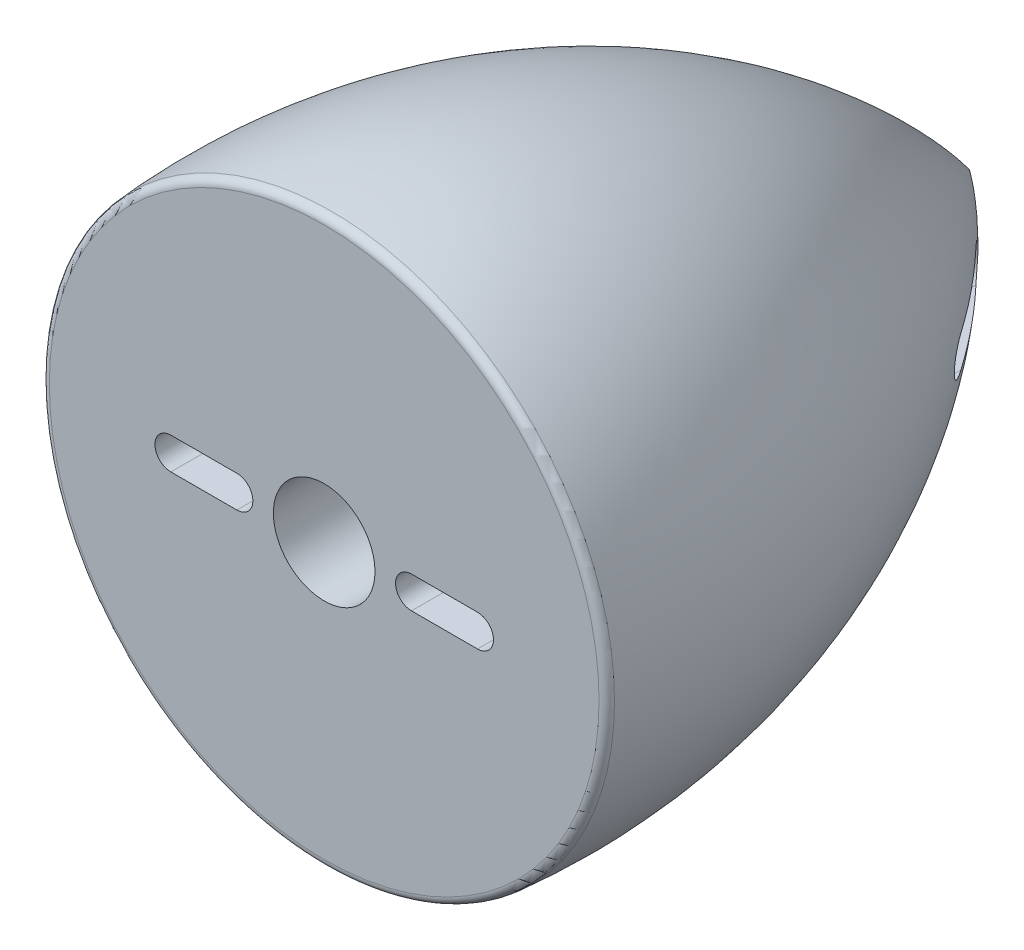
SolidWorks part; units mm, degrees
material "Pine"
ref_plane "Front Plane" through (0, 0, 0) normal (0, 0, 1) x (1, 0, 0)
ref_plane "Top Plane" through (0, 0, 0) normal (0, 1, 0) x (1, 0, 0)
ref_plane "Right Plane" through (0, 0, 0) normal (1, 0, 0) x (0, 0, -1)
ref_plane "Plane1" through (0, 0, -61.468) normal (0, 0, 1) x (1, 0, 0)
sketch "Sketch9" plane through (0, 0, 0) normal (1, 0, 0) x (0, 0, -1)
  line L3 (0, 0) -> (50.8, 0)
  line L4 (0, 0) -> (0, 22.225)
  arc A1 (0, 22.225) -> (50.8, 0) centre (5.1737, -35.1191) cw
  dimension "D1" = 22.225
  dimension "D2" = 50.8
revolve "Revolve2" add sketch "Sketch9" angle 360 about L3
fillet "Fillet4" radius 0.635 1 edges at (22.225, 0, 0)
sketch "Sketch10" plane through (0, 0, 0) normal (0, 0, 1) x (1, 0, 0)
  circle A0 centre (0, 0) radius 4.0005
  dimension "D1" = 8.001
extrude "Cut-Extrude5" cut sketch "Sketch10" against normal blind 11.684 contours A0
sketch "Sketch11" plane through (0, 0, 0) normal (0, 0, 1) x (1, 0, 0)
  line L0 (0, -24.7037) -> (0, 24.7037) construction
  line L1 (6.8726, 1.2693) -> (12.0736, 1.2693)
  line L3 (6.8726, -1.2389) -> (12.0736, -1.2389)
  line L5 (6.8726, 1.2693) -> (12.0736, -1.2389) construction
  line L6 (6.8726, -1.2389) -> (12.0736, 1.2693) construction
  line L7 (-6.8726, -1.2389) -> (-12.0736, 1.2693) construction
  line L8 (-6.8726, 1.2693) -> (-12.0736, -1.2389) construction
  line L9 (-6.8726, 1.2693) -> (-12.0736, 1.2693)
  line L10 (-6.8726, -1.2389) -> (-12.0736, -1.2389)
  arc A0 (12.0736, 1.2693) -> (12.0736, -1.2389) centre (12.0736, 0.0152) cw
  arc A1 (6.8726, 1.2693) -> (6.8726, -1.2389) centre (6.8726, 0.0152) ccw
  arc A2 (-6.8726, 1.2693) -> (-6.8726, -1.2389) centre (-6.8726, 0.0152) cw
  arc A3 (-12.0736, 1.2693) -> (-12.0736, -1.2389) centre (-12.0736, 0.0152) ccw
  point P0 (9.4731, 0.0152)
  point P15 (-9.4731, 0.0152)
extrude "Cut-Extrude6" cut sketch "Sketch11" against normal blind 82.55
